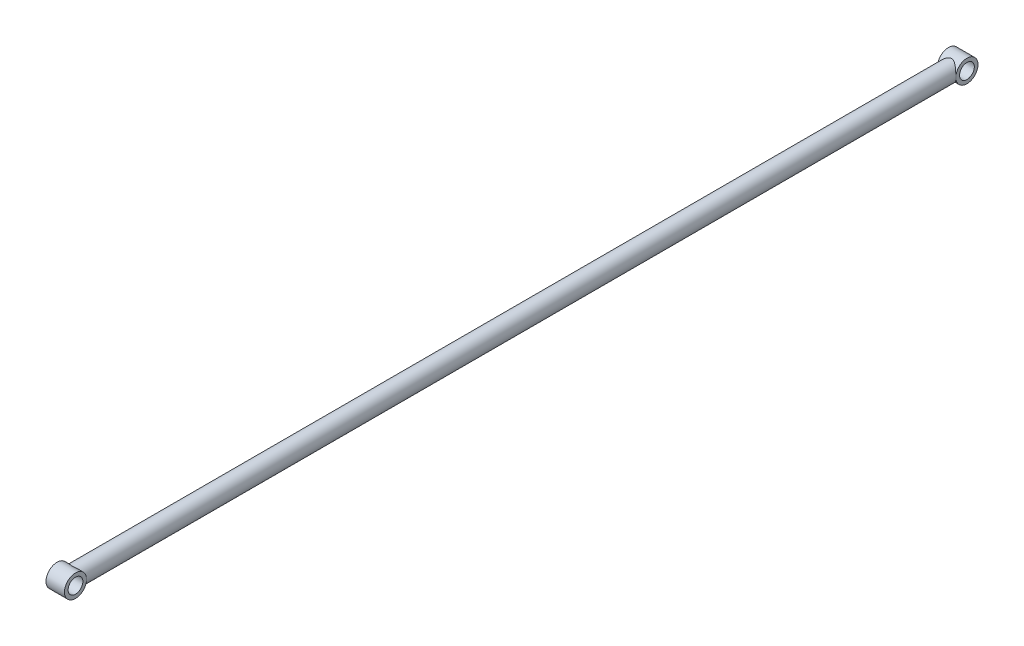
SolidWorks part; units mm, degrees
ref_plane "Front Plane" through (0, 0, 0) normal (0, 0, 1) x (1, 0, 0)
ref_plane "Top Plane" through (0, 0, 0) normal (0, 1, 0) x (1, 0, 0)
ref_plane "Right Plane" through (0, 0, 0) normal (1, 0, 0) x (0, 0, -1)
sketch "Sketch3" plane through (0, 0, 0) normal (0, 0, 1) x (1, 0, 0)
  circle A0 centre (0, 0) radius 5
  dimension "D1" = 10
extrude "Boss-Extrude1" add sketch "Sketch3" along normal blind 483
sketch "Sketch4" plane through (0, 0, 0) normal (1, 0, 0) x (0, 0, -1)
  line L0 (-483, 5) -> (-483, -5) construction
  circle A0 centre (-483, 0) radius 6
  circle A1 centre (0, 0) radius 6
  dimension "D1" = 12
  dimension "D2" = 12
extrude "Boss-Extrude2" add sketch "Sketch4" along normal mid plane 10
sketch "Sketch5" plane through (5, 0, 0) normal (1, 0, 0) x (0, 0, -1)
  circle A0 centre (-483, 0) radius 4
  circle A1 centre (0, 0) radius 3.9999
  dimension "D1" = 8
  dimension "D2" = 7.9999
extrude "Cut-Extrude1" cut sketch "Sketch5" against normal blind 12
